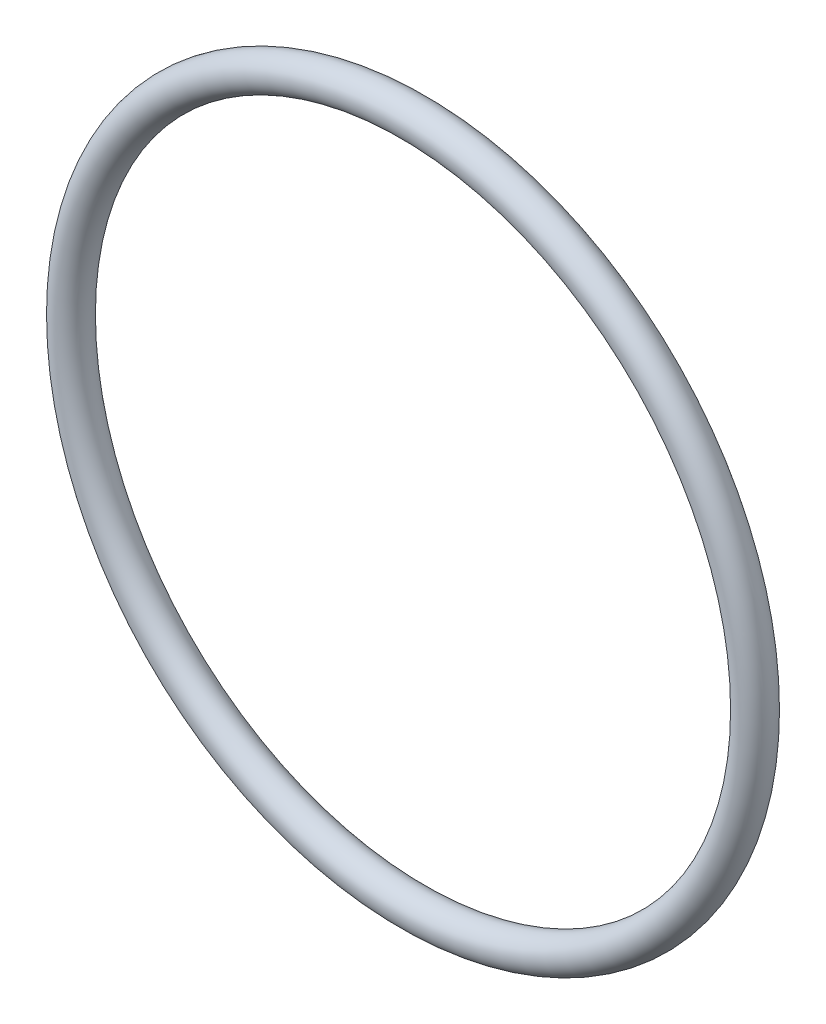
SolidWorks part; units mm, degrees
material "Silicon Rubber"
ref_plane "Front Plane" through (0, 0, 0) normal (0, 0, 1) x (1, 0, 0)
ref_plane "Top Plane" through (0, 0, 0) normal (0, 1, 0) x (1, 0, 0)
ref_plane "Right Plane" through (0, 0, 0) normal (1, 0, 0) x (0, 0, -1)
sketch "Sketch1" plane through (0, 0, 0) normal (0, 1, 0) x (1, 0, 0)
  line L0 (0, 45.0261) -> (0, -33.3281) construction
  line L1 (0, 0) -> (15.494, 0) construction
  line L2 (15.494, 0) -> (16.3195, 0) construction
  circle A0 centre (16.3195, 0) radius 0.8255
  dimension "D1" = 15.494
  dimension "D2" = 0.8255
revolve "Revolve1" add sketch "Sketch1" angle 360 about L0
